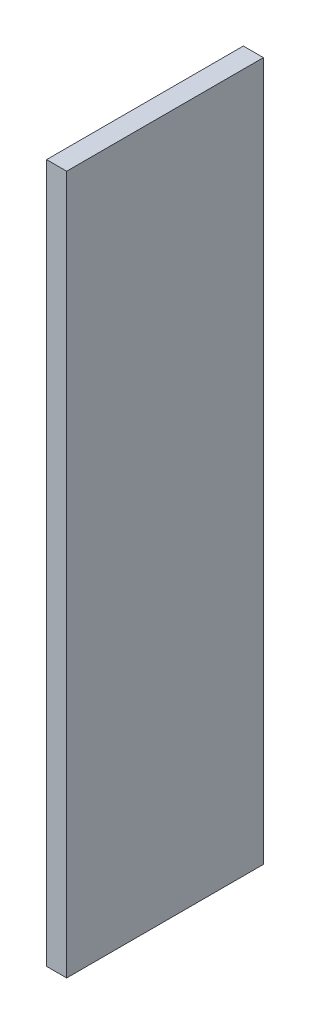
SolidWorks part; units mm, degrees
ref_plane "Front Plane" through (0, 0, 0) normal (0, 0, 1) x (1, 0, 0)
ref_plane "Top Plane" through (0, 0, 0) normal (0, 1, 0) x (1, 0, 0)
ref_plane "Right Plane" through (0, 0, 0) normal (1, 0, 0) x (0, 0, -1)
sketch "Sketch1" plane through (0, 0, 0) normal (-1, 0, 0) x (0, 0, 1)
  line L4 (0.24, 0.87) -> (-0.25, 0.87)
  line L5 (-0.25, 0.87) -> (-0.25, -0.87)
  line L6 (-0.25, -0.87) -> (0.24, -0.87)
  line L7 (0.24, -0.87) -> (0.24, 0.87)
  line L8 (0.24, 0.87) -> (-0.25, 0.87)
  line L9 (-0.25, 0.87) -> (-0.25, -0.87)
  line L10 (-0.25, -0.87) -> (0.24, -0.87)
  line L11 (0.24, -0.87) -> (0.24, 0.87)
  dimension "D1" = 0
extrude "Boss-Extrude1" add sketch "Sketch1" against normal up to surface (0.05 mm away)
